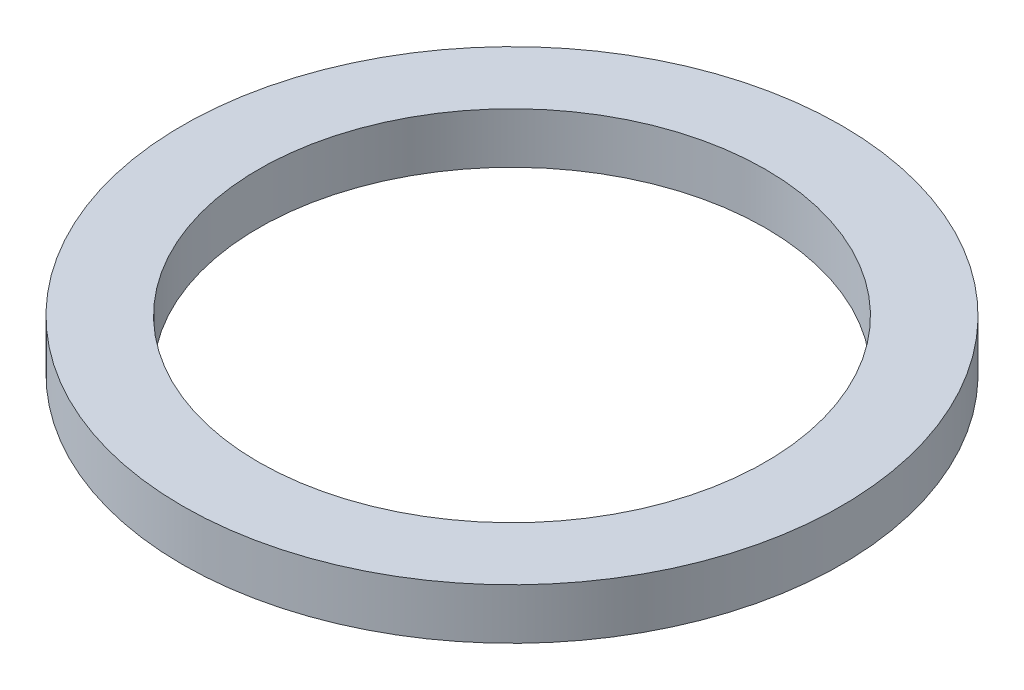
SolidWorks part; units mm, degrees
ref_plane "Спереди" through (0, 0, 0) normal (0, 0, 1) x (1, 0, 0)
ref_plane "Сверху" through (0, 0, 0) normal (0, 1, 0) x (1, 0, 0)
ref_plane "Справа" through (0, 0, 0) normal (1, 0, 0) x (0, 0, -1)
sketch "Эскиз1" plane through (0, 0, 0) normal (0, 1, 0) x (1, 0, 0)
  circle A0 centre (0, 0) radius 20
  circle A1 centre (0, 0) radius 26
  dimension "D1" = 52
  dimension "D2" = 40
extrude "тело" add sketch "Эскиз1" along normal blind 4
